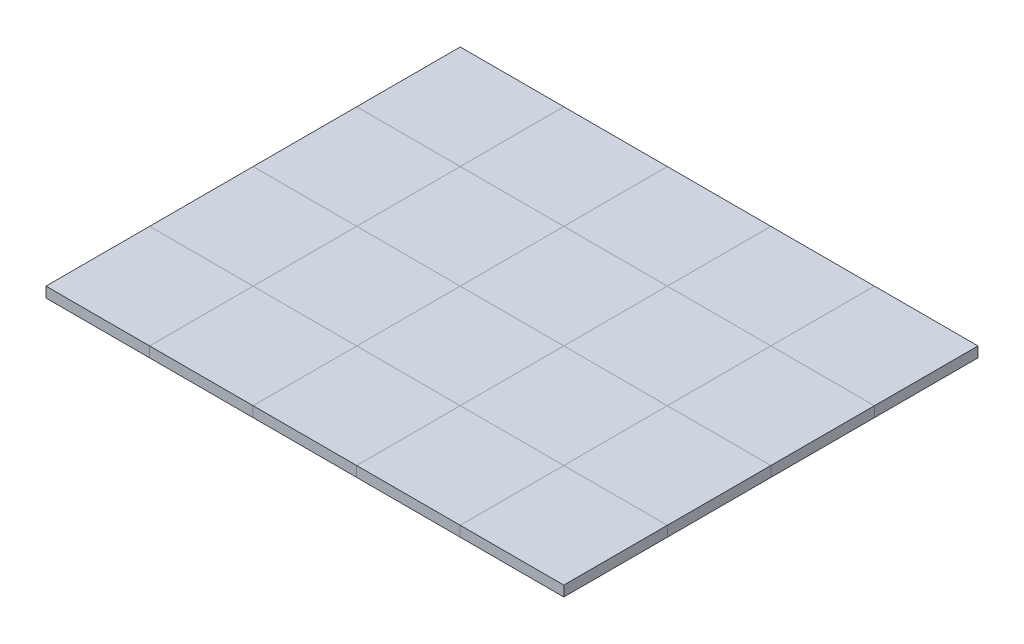
SolidWorks part; units mm, degrees
other "Camera1"
ref_plane "Front Plane" through (0, 0, 0) normal (0, 0, 1) x (1, 0, 0)
ref_plane "Top Plane" through (0, 0, 0) normal (0, 1, 0) x (1, 0, 0)
ref_plane "Right Plane" through (0, 0, 0) normal (1, 0, 0) x (0, 0, -1)
sketch "Sketch1" plane through (0, 0, 0) normal (0, 1, 0) x (1, 0, 0)
  line L1 (0, 0) -> (50, 0)
  line L2 (0, 0) -> (0, 50)
  line L3 (0, 50) -> (50, 50)
  line L4 (50, 0) -> (50, 50)
  dimension "D1" = 50
extrude "Boss-Extrude1" add sketch "Sketch1" along normal blind 5
pattern_linear "LPattern1" count 5 spacing 50 along (1, 0, 0) count 4 spacing 50 along (0, 0, -1) of "Boss-Extrude1"
